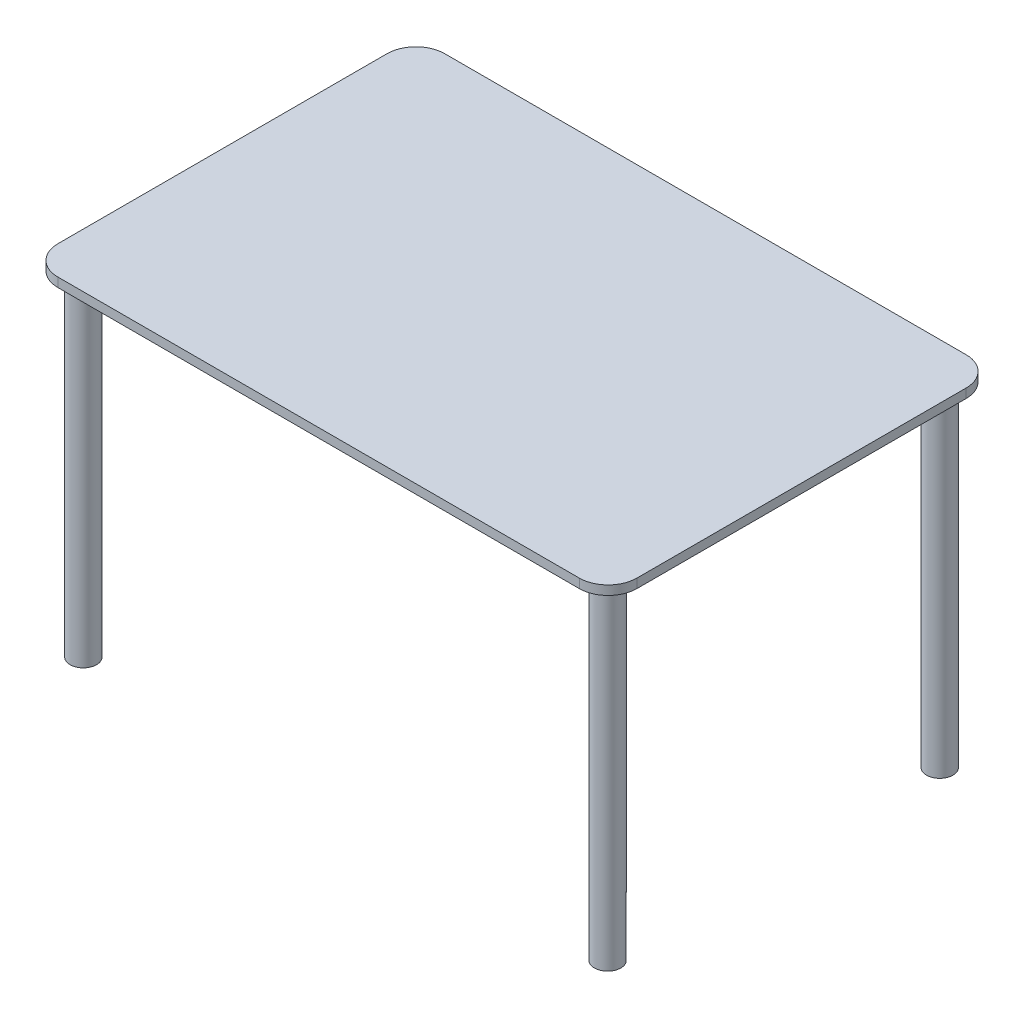
SolidWorks part; units mm, degrees
ref_plane "Front Plane" through (0, 0, 0) normal (0, 0, 1) x (1, 0, 0)
ref_plane "Top Plane" through (0, 0, 0) normal (0, 1, 0) x (1, 0, 0)
ref_plane "Right Plane" through (0, 0, 0) normal (1, 0, 0) x (0, 0, -1)
sketch "Sketch1" plane through (0, 0, 0) normal (0, 1, 0) x (1, 0, 0)
  line L1 (-602.5, -402.5) -> (602.5, -402.5)
  line L2 (-602.5, -402.5) -> (-602.5, 402.5)
  line L3 (-602.5, 402.5) -> (602.5, 402.5)
  line L4 (602.5, -402.5) -> (602.5, 402.5)
  line L5 (-602.5, -402.5) -> (602.5, 402.5) construction
  line L6 (-602.5, 402.5) -> (602.5, -402.5) construction
  point P0 (0, 0)
  dimension "D1" = 805
  dimension "D2" = 1205
extrude "Boss-Extrude1" add sketch "Sketch1" along normal blind 19 contours L2 L1 L4 L3
sketch "Sketch2" plane through (0, 0, 0) normal (0, -1, 0) x (-1, 0, 0)
  line L0 (602.5, -402.5) -> (573.5, -402.5)
  line L1 (602.5, -402.5) -> (-602.5, -402.5) construction
  line L2 (602.5, -402.5) -> (602.5, -373.5)
  line L3 (602.5, -402.5) -> (602.5, 402.5) construction
  line L4 (-602.5, -402.5) -> (-573.5, -402.5)
  line L5 (-602.5, -402.5) -> (-602.5, -373.5)
  line L6 (-602.5, -402.5) -> (-602.5, 402.5) construction
  line L7 (-573.5, 402.5) -> (-602.5, 402.5)
  line L8 (602.5, 402.5) -> (-602.5, 402.5) construction
  line L9 (-602.5, 402.5) -> (-602.5, 373.5)
  line L10 (602.5, 373.5) -> (602.5, 402.5)
  line L11 (602.5, 402.5) -> (573.5, 402.5)
  line L12 (573.5, 402.5) -> (518.5, 402.5)
  line L13 (573.5, 373.5) -> (573.5, 318.5)
  line L14 (573.5, 402.5) -> (573.5, 373.5)
  line L15 (546, 373.5) -> (546, 318.5)
  line L16 (573.5, 373.5) -> (518.5, 373.5)
  line L17 (573.5, 373.5) -> (573.5, 318.5)
  line L18 (573.5, 318.5) -> (518.5, 318.5)
  line L19 (518.5, 373.5) -> (518.5, 318.5)
  line L20 (-544.1205, 373.5) -> (-544.1205, 318.5)
  line L21 (-571.6205, 373.5) -> (-516.6205, 373.5)
  line L22 (-571.6205, 373.5) -> (-571.6205, 318.5)
  line L23 (-571.6205, 318.5) -> (-516.6205, 318.5)
  line L24 (-516.6205, 373.5) -> (-516.6205, 318.5)
  line L25 (-546, -374.5892) -> (-546, -319.5892)
  line L26 (-573.5, -374.5892) -> (-518.5, -374.5892)
  line L27 (-573.5, -374.5892) -> (-573.5, -319.5892)
  line L28 (-573.5, -319.5892) -> (-518.5, -319.5892)
  line L29 (-518.5, -374.5892) -> (-518.5, -319.5892)
  line L30 (546, -373.5) -> (546, -318.5)
  line L31 (573.5, -373.5) -> (518.5, -373.5)
  line L32 (573.5, -373.5) -> (573.5, -318.5)
  line L33 (573.5, -318.5) -> (518.5, -318.5)
  line L34 (518.5, -373.5) -> (518.5, -318.5)
  circle A0 centre (546, 346) radius 27.5
  circle A1 centre (-544.1205, 346) radius 27.5
  circle A2 centre (-546, -347.0892) radius 27.5
  circle A3 centre (546, -346) radius 27.5
  dimension "D1" = 29
  dimension "D2" = 29
  dimension "D3" = 29
  dimension "D4" = 29
  dimension "D5" = 29
  dimension "D6" = 29
  dimension "D7" = 55
  dimension "D8" = 29
  dimension "D9" = 55
  dimension "D10" = 55
  dimension "D11" = 55
  dimension "D12" = 55
  dimension "D13" = 55
  dimension "D14" = 55
  dimension "D15" = 29
  dimension "D16" = 55
extrude "Boss-Extrude2" add sketch "Sketch2" along normal blind 696 contours A3 | A2 | A1 | A0
fillet "Fillet1" radius 60 4 edges at (602.5, 9.5, 402.5) (-602.5, 9.5, 402.5) (-602.5, 9.5, -402.5) (602.5, 9.5, -402.5)
